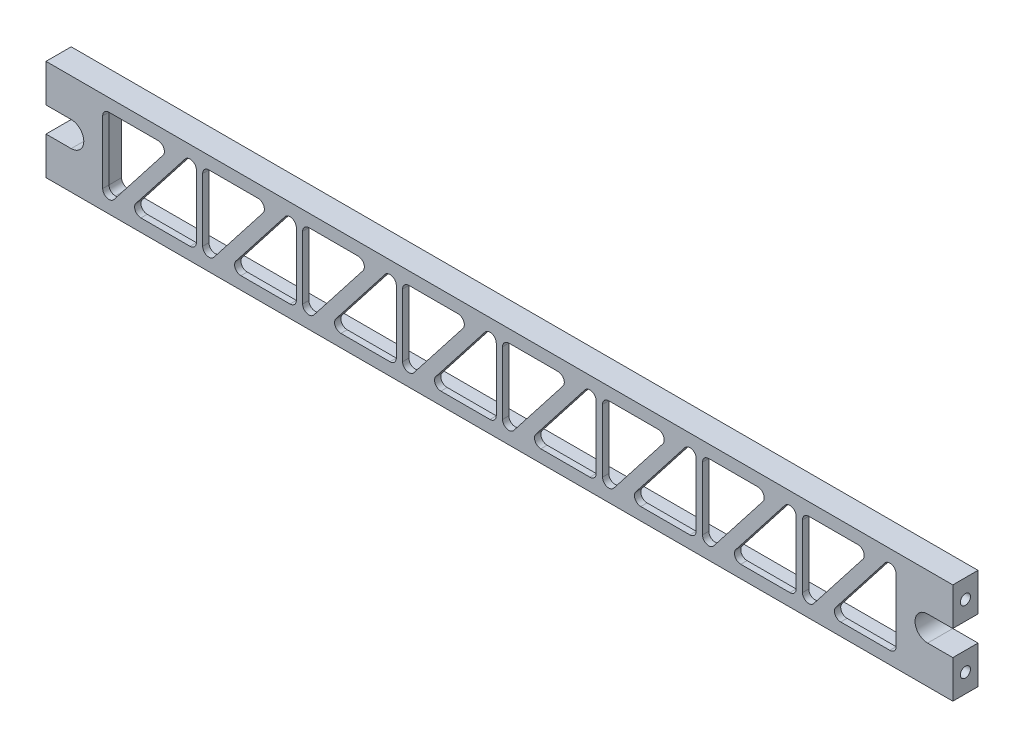
SolidWorks part; units mm, degrees
material "6061 Alloy"
ref_plane "Front Plane" through (0, 0, 0) normal (0, 0, 1) x (1, 0, 0)
ref_plane "Top Plane" through (0, 0, 0) normal (0, 1, 0) x (1, 0, 0)
ref_plane "Right Plane" through (0, 0, 0) normal (1, 0, 0) x (0, 0, -1)
sketch "Sketch1" plane through (0, 0, 0) normal (1, 0, 0) x (0, 0, -1)
  line L1 (0, 0) -> (12.7, 0)
  line L2 (0, 0) -> (0, 50.8)
  line L3 (0, 50.8) -> (12.7, 50.8)
  line L4 (12.7, 0) -> (12.7, 50.8)
  dimension "D1" = 12.7
  dimension "D2" = 50.8
extrude "Boss-Extrude1" add sketch "Sketch1" along normal mid plane 457.2
hole_wizard "1/4-20 Tapped Hole1" positions "3DSketch1" profile "Sketch2" tap size "1/4-20" standard "ANSI Inch"
sketch3d "3DSketch1"
  line L2 (228.6, 9.525, -6.35) -> (228.6, 41.275, -6.35) construction
  line L4 (228.6, 41.275, -6.35) -> (228.6, 50.8, -6.35) construction
  line L5 (228.6, 50.8, -12.7) -> (228.6, 50.8, 0) construction
  line L8 (228.6, 9.525, -6.35) -> (228.6, 0, -6.35) construction
  line L9 (228.6, 0, 0) -> (228.6, 0, -12.7) construction
  point P0 (228.6, 41.275, -6.35)
  point P2 (228.6, 9.525, -6.35)
  point P4 (-228.6, 9.525, -6.35)
  point P6 (-228.6, 41.275, -6.35)
  dimension "D1" = 31.75
sketch "Sketch2" plane through (228.6, 41.275, -6.35) normal (0, 1, 0) x (0, 0, -1)
  line L0 (0, 0) -> (0, 20.5838)
  line L1 (0, 20.5838) -> (2.5527, 19.05)
  line L2 (2.5527, 19.05) -> (2.5527, 0)
  line L5 (2.5527, 0) -> (0, 0)
  line L10 (0, 20.5838) -> (-2.5527, 19.05) construction
  line L11 (0, -6.35) -> (0, 107.95) construction
  dimension "Tap Drill Dia." = 5.1054
  dimension "Tap Drill Depth" = 19.05
  dimension "Drill Angle" = 118
sketch "Sketch4" plane through (0, 0, -12.7) normal (0, 0, -1) x (-1, 0, 0)
  line L0 (0, 0) -> (0, 3.175) construction
  line L1 (200.025, 47.625) -> (-200.025, 47.625)
  line L2 (203.2, 44.45) -> (203.2, 6.35)
  line L3 (200.025, 3.175) -> (-200.025, 3.175)
  line L4 (-203.2, 44.45) -> (-203.2, 6.35)
  line L5 (-228.6, 0) -> (228.6, 0) construction
  line L6 (0, 47.625) -> (0, 50.8) construction
  line L7 (-228.6, 50.8) -> (228.6, 50.8) construction
  line L8 (228.6, 25.4) -> (203.2, 25.4) construction
  line L9 (228.6, 0) -> (228.6, 50.8) construction
  line L10 (-228.6, 25.4) -> (-203.2, 25.4) construction
  line L11 (-228.6, 0) -> (-228.6, 50.8) construction
  arc A0 (-200.025, 3.175) -> (-203.2, 6.35) centre (-200.025, 6.35) cw
  arc A1 (-200.025, 47.625) -> (-203.2, 44.45) centre (-200.025, 44.45) ccw
  arc A2 (203.2, 6.35) -> (200.025, 3.175) centre (200.025, 6.35) cw
  arc A3 (200.025, 47.625) -> (203.2, 44.45) centre (200.025, 44.45) cw
  dimension "D1" = 3.175
  dimension "D2" = 3.175
  dimension "D3" = 25.4
extrude "Cut-Extrude1" cut sketch "Sketch4" against normal blind 9.525
sketch "Sketch5" plane through (0, 0, -3.175) normal (0, 0, -1) x (-1, 0, 0)
  line L0 (-200.025, 41.275) -> (-200.025, 9.525)
  line L1 (-196.85, 6.35) -> (-172.0797, 6.35)
  line L2 (-169.5764, 11.478) -> (-194.3467, 43.228)
  line L3 (-183.2455, 39.322) -> (-158.4752, 7.572)
  line L4 (-152.7969, 9.525) -> (-152.7969, 41.275)
  line L5 (-155.9719, 44.45) -> (-180.7422, 44.45)
  line L7 (-168.357, 44.45) -> (-168.357, 47.625) construction
  line L8 (200.025, 47.625) -> (-200.025, 47.625) construction
  line L10 (-184.4648, 6.35) -> (-184.4648, 3.175) construction
  line L11 (-200.025, 3.175) -> (200.025, 3.175) construction
  line L13 (-200.025, 25.4) -> (-203.2, 25.4) construction
  line L14 (-203.2, 44.45) -> (-203.2, 6.35) construction
  line L15 (-181.9615, 27.353) -> (-176.955, 31.259) construction
  line L16 (-149.6219, 25.4) -> (-152.7969, 25.4) construction
  line L17 (-149.6219, 41.275) -> (-149.6219, 9.525)
  line L18 (-119.1733, 11.478) -> (-143.9436, 43.228)
  line L19 (-146.4469, 6.35) -> (-121.6765, 6.35)
  line L20 (-131.5584, 27.353) -> (-126.5518, 31.259) construction
  line L21 (-132.8424, 39.322) -> (-108.072, 7.572)
  line L22 (-105.5687, 44.45) -> (-130.3391, 44.45)
  line L23 (-102.3938, 9.525) -> (-102.3938, 41.275)
  line L24 (-117.9539, 44.45) -> (-117.9539, 47.625) construction
  line L25 (-134.0617, 6.35) -> (-134.0617, 3.175) construction
  line L26 (-99.2187, 25.4) -> (-102.3937, 25.4) construction
  line L27 (-99.2187, 41.275) -> (-99.2187, 9.525)
  line L28 (-68.7701, 11.478) -> (-93.5405, 43.228)
  line L29 (-96.0437, 6.35) -> (-71.2734, 6.35)
  line L30 (-81.1553, 27.353) -> (-76.1487, 31.259) construction
  line L31 (-82.4392, 39.322) -> (-57.6689, 7.572)
  line L32 (-55.1656, 44.45) -> (-79.936, 44.45)
  line L33 (-51.9906, 9.525) -> (-51.9906, 41.275)
  line L34 (-67.5508, 44.45) -> (-67.5508, 47.625) construction
  line L35 (-83.6586, 6.35) -> (-83.6586, 3.175) construction
  line L36 (-48.8156, 25.4) -> (-51.9906, 25.4) construction
  line L37 (-48.8156, 41.275) -> (-48.8156, 9.525)
  line L38 (-18.367, 11.478) -> (-43.1373, 43.228)
  line L39 (-45.6406, 6.35) -> (-20.8703, 6.35)
  line L40 (-30.7522, 27.353) -> (-25.7456, 31.259) construction
  line L41 (-32.0361, 39.322) -> (-7.2658, 7.572)
  line L42 (-4.7625, 44.45) -> (-29.5328, 44.45)
  line L43 (-1.5875, 9.525) -> (-1.5875, 41.275)
  line L44 (-17.1477, 44.45) -> (-17.1477, 47.625) construction
  line L45 (-33.2555, 6.35) -> (-33.2555, 3.175) construction
  line L46 (1.5875, 25.4) -> (-1.5875, 25.4) construction
  line L47 (1.5875, 41.275) -> (1.5875, 9.525)
  line L48 (32.0361, 11.478) -> (7.2658, 43.228)
  line L49 (4.7625, 6.35) -> (29.5328, 6.35)
  line L50 (19.651, 27.353) -> (24.6575, 31.259) construction
  line L51 (18.367, 39.322) -> (43.1373, 7.572)
  line L52 (45.6406, 44.45) -> (20.8703, 44.45)
  line L53 (48.8156, 9.525) -> (48.8156, 41.275)
  line L54 (33.2555, 44.45) -> (33.2555, 47.625) construction
  line L55 (17.1477, 6.35) -> (17.1477, 3.175) construction
  line L56 (51.9906, 25.4) -> (48.8156, 25.4) construction
  line L57 (51.9906, 41.275) -> (51.9906, 9.525)
  line L58 (82.4392, 11.478) -> (57.6689, 43.228)
  line L59 (55.1656, 6.35) -> (79.936, 6.35)
  line L60 (70.0541, 27.353) -> (75.0607, 31.259) construction
  line L61 (68.7701, 39.322) -> (93.5405, 7.572)
  line L62 (96.0438, 44.45) -> (71.2734, 44.45)
  line L63 (99.2187, 9.525) -> (99.2187, 41.275)
  line L64 (83.6586, 44.45) -> (83.6586, 47.625) construction
  line L65 (67.5508, 6.35) -> (67.5508, 3.175) construction
  line L66 (102.3937, 25.4) -> (99.2187, 25.4) construction
  line L67 (102.3937, 41.275) -> (102.3937, 9.525)
  line L68 (132.8424, 11.478) -> (108.072, 43.228)
  line L69 (105.5687, 6.35) -> (130.3391, 6.35)
  line L71 (120.4572, 27.353) -> (125.4638, 31.259) construction
  line L77 (119.1733, 39.322) -> (143.9436, 7.572)
  line L83 (146.4469, 44.45) -> (121.6765, 44.45)
  line L89 (149.6219, 9.525) -> (149.6219, 41.275)
  line L95 (134.0617, 44.45) -> (134.0617, 47.625) construction
  line L101 (117.9539, 6.35) -> (117.9539, 3.175) construction
  line L107 (152.7969, 25.4) -> (149.6219, 25.4) construction
  line L113 (152.7969, 41.275) -> (152.7969, 9.525)
  line L115 (183.2455, 11.478) -> (158.4752, 43.228)
  line L117 (155.9719, 6.35) -> (180.7422, 6.35)
  line L119 (170.8603, 27.353) -> (175.8669, 31.259) construction
  line L121 (169.5764, 39.322) -> (194.3467, 7.572)
  line L123 (196.85, 44.45) -> (172.0797, 44.45)
  line L125 (200.025, 9.525) -> (200.025, 41.275)
  line L126 (184.4648, 44.45) -> (184.4648, 47.625) construction
  line L127 (168.357, 6.35) -> (168.357, 3.175) construction
  line L128 (200.025, 25.4) -> (203.2, 25.4) construction
  line L129 (203.2, 6.35) -> (203.2, 44.45) construction
  arc A0 (-183.2455, 39.322) -> (-180.7422, 44.45) centre (-180.7422, 41.275) cw
  arc A1 (-152.7969, 41.275) -> (-155.9719, 44.45) centre (-155.9719, 41.275) ccw
  arc A2 (-158.4752, 7.572) -> (-152.7969, 9.525) centre (-155.9719, 9.525) ccw
  arc A3 (-172.0797, 6.35) -> (-169.5764, 11.478) centre (-172.0797, 9.525) ccw
  arc A4 (-200.025, 9.525) -> (-196.85, 6.35) centre (-196.85, 9.525) ccw
  arc A5 (-200.025, 41.275) -> (-194.3467, 43.228) centre (-196.85, 41.275) cw
  arc A6 (-149.6219, 41.275) -> (-143.9436, 43.228) centre (-146.4469, 41.275) cw
  arc A7 (-121.6765, 6.35) -> (-119.1733, 11.478) centre (-121.6765, 9.525) ccw
  arc A8 (-149.6219, 9.525) -> (-146.4469, 6.35) centre (-146.4469, 9.525) ccw
  arc A9 (-132.8424, 39.322) -> (-130.3391, 44.45) centre (-130.3391, 41.275) cw
  arc A10 (-102.3938, 41.275) -> (-105.5687, 44.45) centre (-105.5687, 41.275) ccw
  arc A11 (-108.072, 7.572) -> (-102.3938, 9.525) centre (-105.5687, 9.525) ccw
  arc A12 (-99.2187, 41.275) -> (-93.5405, 43.228) centre (-96.0437, 41.275) cw
  arc A13 (-71.2734, 6.35) -> (-68.7701, 11.478) centre (-71.2734, 9.525) ccw
  arc A14 (-99.2187, 9.525) -> (-96.0437, 6.35) centre (-96.0437, 9.525) ccw
  arc A15 (-82.4392, 39.322) -> (-79.936, 44.45) centre (-79.936, 41.275) cw
  arc A16 (-51.9906, 41.275) -> (-55.1656, 44.45) centre (-55.1656, 41.275) ccw
  arc A17 (-57.6689, 7.572) -> (-51.9906, 9.525) centre (-55.1656, 9.525) ccw
  arc A18 (-48.8156, 41.275) -> (-43.1373, 43.228) centre (-45.6406, 41.275) cw
  arc A19 (-20.8703, 6.35) -> (-18.367, 11.478) centre (-20.8703, 9.525) ccw
  arc A20 (-48.8156, 9.525) -> (-45.6406, 6.35) centre (-45.6406, 9.525) ccw
  arc A21 (-32.0361, 39.322) -> (-29.5328, 44.45) centre (-29.5328, 41.275) cw
  arc A22 (-1.5875, 41.275) -> (-4.7625, 44.45) centre (-4.7625, 41.275) ccw
  arc A23 (-7.2658, 7.572) -> (-1.5875, 9.525) centre (-4.7625, 9.525) ccw
  arc A24 (1.5875, 41.275) -> (7.2658, 43.228) centre (4.7625, 41.275) cw
  arc A25 (29.5328, 6.35) -> (32.0361, 11.478) centre (29.5328, 9.525) ccw
  arc A26 (1.5875, 9.525) -> (4.7625, 6.35) centre (4.7625, 9.525) ccw
  arc A27 (18.367, 39.322) -> (20.8703, 44.45) centre (20.8703, 41.275) cw
  arc A28 (48.8156, 41.275) -> (45.6406, 44.45) centre (45.6406, 41.275) ccw
  arc A29 (43.1373, 7.572) -> (48.8156, 9.525) centre (45.6406, 9.525) ccw
  arc A30 (51.9906, 41.275) -> (57.6689, 43.228) centre (55.1656, 41.275) cw
  arc A31 (79.936, 6.35) -> (82.4392, 11.478) centre (79.936, 9.525) ccw
  arc A32 (51.9906, 9.525) -> (55.1656, 6.35) centre (55.1656, 9.525) ccw
  arc A33 (68.7701, 39.322) -> (71.2734, 44.45) centre (71.2734, 41.275) cw
  arc A34 (99.2187, 41.275) -> (96.0438, 44.45) centre (96.0437, 41.275) ccw
  arc A35 (93.5405, 7.572) -> (99.2187, 9.525) centre (96.0437, 9.525) ccw
  arc A36 (102.3937, 41.275) -> (108.072, 43.228) centre (105.5687, 41.275) cw
  arc A37 (130.3391, 6.35) -> (132.8424, 11.478) centre (130.3391, 9.525) ccw
  arc A38 (102.3937, 9.525) -> (105.5687, 6.35) centre (105.5687, 9.525) ccw
  arc A39 (119.1733, 39.322) -> (121.6765, 44.45) centre (121.6765, 41.275) cw
  arc A40 (149.6219, 41.275) -> (146.4469, 44.45) centre (146.4469, 41.275) ccw
  arc A41 (143.9436, 7.572) -> (149.6219, 9.525) centre (146.4469, 9.525) ccw
  arc A42 (152.7969, 41.275) -> (158.4752, 43.228) centre (155.9719, 41.275) cw
  arc A43 (180.7422, 6.35) -> (183.2455, 11.478) centre (180.7422, 9.525) ccw
  arc A44 (152.7969, 9.525) -> (155.9719, 6.35) centre (155.9719, 9.525) ccw
  arc A45 (169.5764, 39.322) -> (172.0797, 44.45) centre (172.0797, 41.275) cw
  arc A46 (200.025, 41.275) -> (196.85, 44.45) centre (196.85, 41.275) ccw
  arc A47 (194.3467, 7.572) -> (200.025, 9.525) centre (196.85, 9.525) ccw
  dimension "D1" = 3.175
  dimension "D2" = 3.175
  dimension "D3" = 6.35
  dimension "D4" = 8
extrude "Cut-Extrude2" cut sketch "Sketch5" against normal through all
sketch "Sketch6" plane through (0, 0, 0) normal (0, 0, 1) x (1, 0, 0)
  line L0 (0, 0) -> (0, 50.8) construction
  line L1 (228.6, 50.8) -> (-228.6, 50.8) construction
  line L2 (-215.9, 31.75) -> (-228.6, 31.75)
  line L3 (-228.6, 50.8) -> (-228.6, 0) construction
  line L4 (-228.6, 31.75) -> (-228.6, 19.05)
  line L5 (-228.6, 19.05) -> (-215.9, 19.05)
  line L6 (228.6, 19.05) -> (215.9, 19.05)
  line L7 (-203.2, 6.35) -> (-203.2, 44.45) construction
  line L8 (228.6, 31.75) -> (228.6, 19.05)
  line L9 (215.9, 31.75) -> (228.6, 31.75)
  arc A0 (-215.9, 19.05) -> (-215.9, 31.75) centre (-215.9, 25.4) ccw
  arc A1 (215.9, 19.05) -> (215.9, 31.75) centre (215.9, 25.4) cw
  point P8 (-228.6, 25.4)
  point P18 (228.6, 25.4)
  point P19 (-209.55, 25.4)
  dimension "D1" = 12.7
  dimension "D2" = 6.35
extrude "Cut-Extrude3" cut sketch "Sketch6" against normal through all
